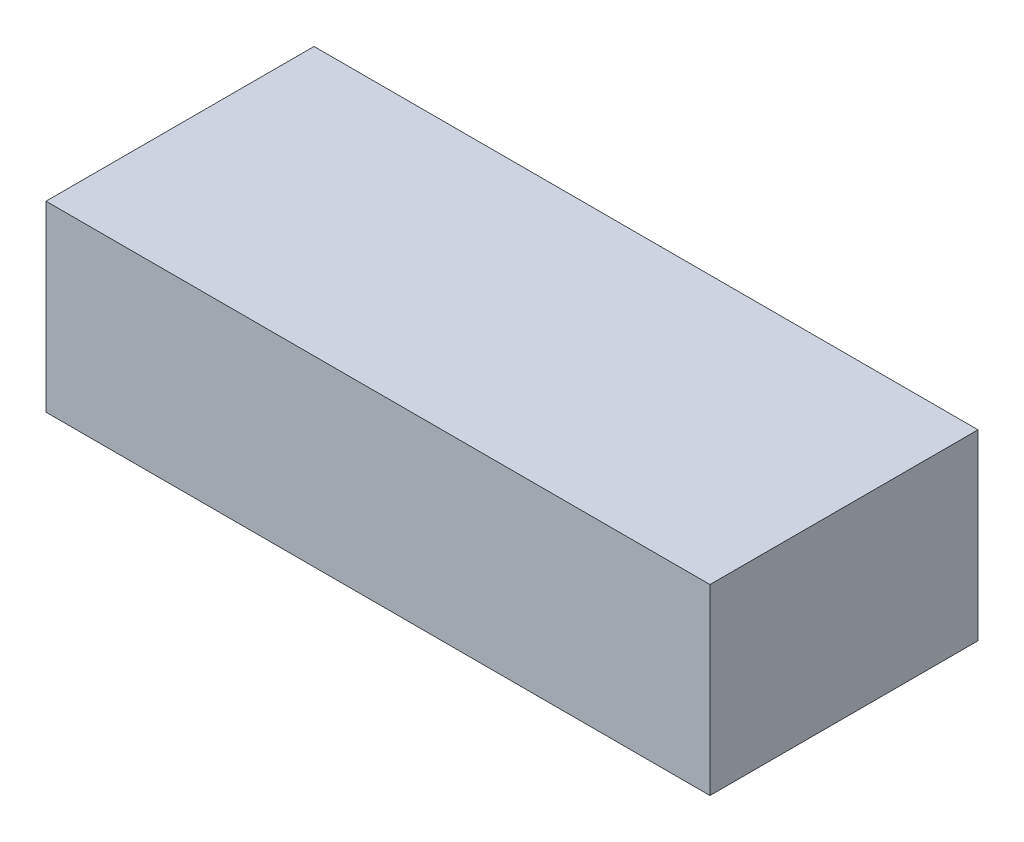
SolidWorks part; units mm, degrees
ref_plane "Front Plane" through (0, 0, 0) normal (0, 0, 1) x (1, 0, 0)
ref_plane "Top Plane" through (0, 0, 0) normal (0, 1, 0) x (1, 0, 0)
ref_plane "Right Plane" through (0, 0, 0) normal (1, 0, 0) x (0, 0, -1)
sketch "Sketch1" plane through (0, 0, 0) normal (0, 1, 0) x (1, 0, 0)
  line L1 (0, 0) -> (218, 0)
  line L2 (0, 0) -> (0, 88)
  line L3 (0, 88) -> (218, 88)
  line L4 (218, 0) -> (218, 88)
  dimension "D1" = 218
  dimension "D2" = 88
extrude "Boss-Extrude1" add sketch "Sketch1" along normal blind 60
